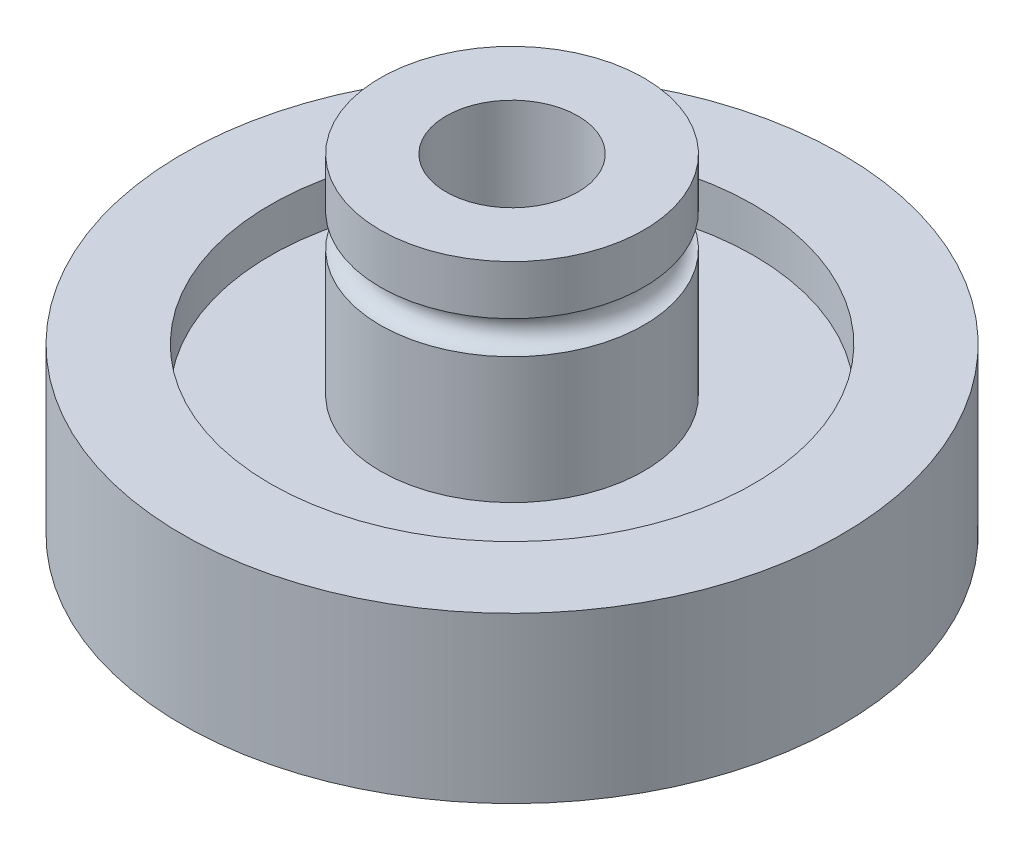
SolidWorks part; units mm, degrees
ref_plane "前视基准面" through (0, 0, 0) normal (0, 0, 1) x (1, 0, 0)
ref_plane "上视基准面" through (0, 0, 0) normal (0, 1, 0) x (1, 0, 0)
ref_plane "右视基准面" through (0, 0, 0) normal (1, 0, 0) x (0, 0, -1)
sketch "草图1" plane through (0, 0, 0) normal (0, 0, 1) x (1, 0, 0)
  line L0 (-12, 30) -> (-12, 15)
  line L1 (-12, 15) -> (-30, 15)
  line L2 (-30, 15) -> (-30, 0)
  line L3 (-30, 0) -> (-6, 0)
  line L4 (-6, 0) -> (-6, 30)
  line L5 (-6, 30) -> (-12, 30)
  line L6 (0, -28.5077) -> (0, 64.8227) construction
  dimension "D1" = 6
  dimension "D2" = 15
  dimension "D3" = 30
  dimension "D4" = 30
  dimension "D5" = 12
  dimension "D6" = 0
revolve "旋转1" add sketch "草图1" angle 360 about L6
sketch "草图2" plane through (0, 0, 0) normal (0, 0, 1) x (1, 0, 0)
  line L0 (-12, 30) -> (-12, 15) construction
  line L1 (30, 15) -> (-30, 15) construction
  line L2 (-22, 15) -> (-12, 15)
  line L3 (-22, 15) -> (-22, 11)
  line L4 (-22, 11) -> (-12, 11)
  line L5 (-12, 15) -> (-12, 11)
  line L6 (-30, 0) -> (30, 0) construction
  line L7 (-22, 0) -> (-12, 0)
  line L8 (-22, 0) -> (-22, 4)
  line L9 (-22, 4) -> (-12, 4)
  line L10 (-12, 0) -> (-12, 4)
  line L11 (12, 30) -> (-12, 30) construction
  line L12 (0, 0) -> (0, 15) construction
  circle A0 centre (-12, 24) radius 1.5
  dimension "D2" = 3
  dimension "D1" = 6
  dimension "D3" = 10
  dimension "D4" = 10
  dimension "D5" = 4
  dimension "D6" = 4
  dimension "D7" = 12
  dimension "D8" = 12
revolve "切除-旋转1" cut sketch "草图2" angle 360 about L12
